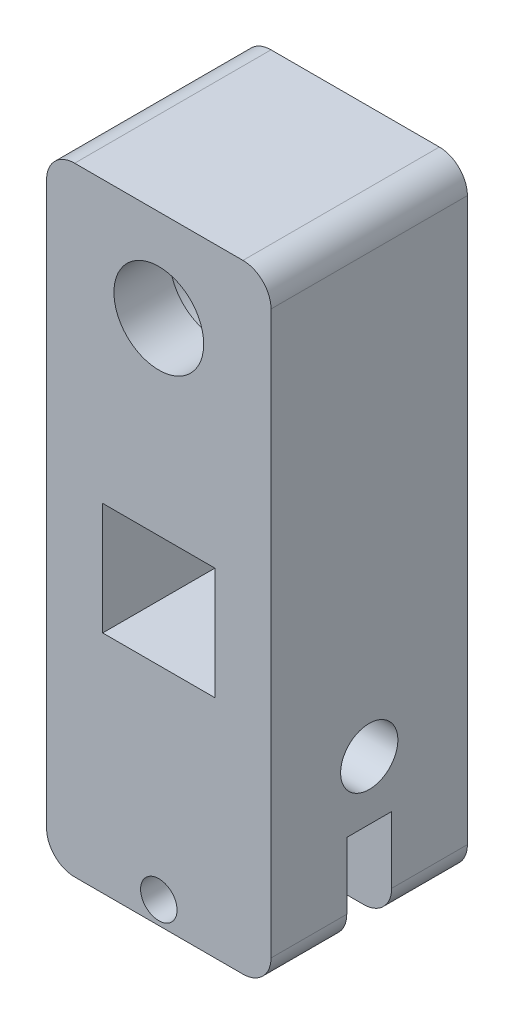
SolidWorks part; units mm, degrees
ref_plane "Alzado" through (0, 0, 0) normal (0, 0, 1) x (1, 0, 0)
ref_plane "Planta" through (0, 0, 0) normal (0, 1, 0) x (1, 0, 0)
ref_plane "Vista lateral" through (0, 0, 0) normal (1, 0, 0) x (0, 0, -1)
sketch "Croquis1" plane through (0, 0, 0) normal (0, 0, 1) x (1, 0, 0)
  line L0 (20, 40.17) -> (20, 89.6091) construction
  line L1 (5, 0) -> (35, 0)
  line L2 (0, 5) -> (0, 40.17)
  line L3 (0, 40.17) -> (40, 40.17)
  line L4 (40, 5) -> (40, 40.17)
  line L5 (20, 0) -> (20, 4) construction
  line L6 (10, 60.17) -> (30, 60.17)
  line L7 (10, 60.17) -> (10, 40.17)
  line L8 (10, 40.17) -> (30, 40.17)
  line L9 (30, 60.17) -> (30, 40.17)
  line L10 (10, 60.17) -> (30, 40.17) construction
  line L11 (10, 40.17) -> (30, 60.17) construction
  line L12 (0, 40.17) -> (40, 40.17)
  line L13 (0, 40.17) -> (0, 105.17)
  line L14 (5, 110.17) -> (35, 110.17)
  line L15 (40, 40.17) -> (40, 105.17)
  circle A0 centre (20, 93.74) radius 12
  circle A1 centre (20, 4) radius 3.25
  arc A2 (5, 0) -> (0, 5) centre (5, 5) cw
  arc A3 (35, 0) -> (40, 5) centre (35, 5) ccw
  arc A4 (35, 110.17) -> (40, 105.17) centre (35, 105.17) cw
  arc A5 (0, 105.17) -> (5, 110.17) centre (5, 105.17) cw
  point P7 (20, 50.17)
  point P21 (0, 0)
  point P24 (40, 0)
  point P29 (0, 110.17)
  dimension "D5" = 6.5
  dimension "D7" = 24
  dimension "D10" = 5
  dimension "D1" = 40
  dimension "D2" = 40.17
  dimension "D3" = 10
  dimension "D4" = 20
  dimension "D6" = 20
  dimension "D8" = 33.57
  dimension "D9" = 70
  dimension "D11" = 4
extrude "Saliente-Extruir1" add sketch "Croquis1" along normal blind 35 contours A5 L13 L3 L7 L6 L9 L15 A4 L14 A0 | L1 A3 L4 L3 L2 A2 A1
sketch "Croquis2" plane through (0, 0, 35) normal (0, 0, 1) x (1, 0, 0)
  line L0 (20, 0) -> (20, 110.17) construction
  line L1 (5, 0) -> (35, 0) construction
  line L2 (5, 110.17) -> (35, 110.17) construction
  circle A0 centre (20, 93.74) radius 12
  circle A1 centre (20, 93.74) radius 8
  dimension "D1" = 24
  dimension "D2" = 4
extrude "Saliente-Extruir2" add sketch "Croquis2" against normal blind 10
sketch "Croquis3" plane through (0, 0, 0) normal (-1, 0, 0) x (0, 0, 1)
  line L0 (17.5, 0) -> (17.5, 16.86) construction
  line L1 (35, 0) -> (0, 0) construction
  line L2 (17.5, 0) -> (17.5, 27.36) construction
  line L3 (13.5, 0) -> (21.5, 0)
  line L4 (13.5, 0) -> (13.5, 16.86)
  line L5 (13.5, 16.86) -> (21.5, 16.86)
  line L6 (21.5, 0) -> (21.5, 16.86)
  line L7 (13.5, 0) -> (21.5, 16.86) construction
  line L8 (13.5, 16.86) -> (21.5, 0) construction
  circle A4 centre (17.5, 27.36) radius 5.1
  point P4 (17.5, 8.43)
  point P17 (35, 0)
  point P24 (0, 110.17)
  dimension "D3" = 0
  dimension "D4" = 10.2
  dimension "D1" = 8
  dimension "D2" = 16.86
  dimension "D5" = 27.36
extrude "Cortar-Extruir2" cut sketch "Croquis3" against normal through all
sketch "Croquis4" plane through (0, 0, 0) normal (-1, 0, 0) x (0, 0, 1)
  circle A0 centre (17.5, 27.36) radius 11
  dimension "D1" = 22
extrude "Cortar-Extruir3" cut sketch "Croquis4" against normal blind 3.5
